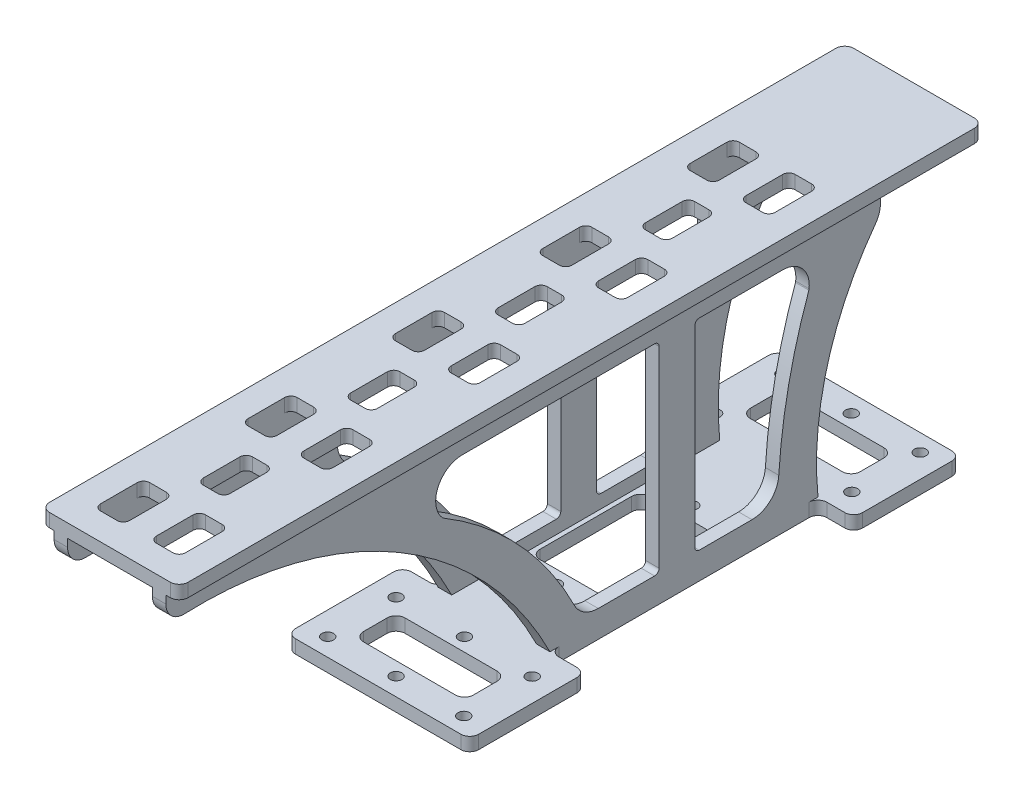
SolidWorks part; units mm, degrees
material "Plain Carbon Steel"
ref_plane "Front" through (0, 0, 0) normal (0, 0, 1) x (1, 0, 0)
ref_plane "Top" through (0, 0, 0) normal (0, 1, 0) x (1, 0, 0)
ref_plane "Right" through (0, 0, 0) normal (1, 0, 0) x (0, 0, -1)
sketch "Sketch1" plane through (0, 0, 0) normal (0, 0, 1) x (1, 0, 0)
  line L0 (0, 0) -> (205, 0)
  line L1 (205, 0) -> (205, 15)
  line L2 (205, 15) -> (180, 15)
  line L3 (180, 15) -> (180, 300)
  line L4 (180, 300) -> (25, 300)
  line L5 (25, 300) -> (25, 15)
  line L6 (25, 15) -> (0, 15)
  line L7 (0, 15) -> (0, 0)
  dimension "D1" = 205
  dimension "D2" = 15
  dimension "D3" = 15
  dimension "D4" = 25
  dimension "D5" = 25
  dimension "D6" = 300
extrude "Boss-Extrude1" add sketch "Sketch1" along normal blind 650
sketch "Sketch3" plane through (0, 0, 0) normal (0, -1, 0) x (1, 0, 0)
  line L0 (205, 325) -> (0, 325) construction
  line L1 (205, 650) -> (205, 0) construction
  line L2 (0, 650) -> (0, 0) construction
  circle A0 centre (26, 70.25) radius 6.5
  circle A1 centre (102.5, 70.25) radius 6.5
  circle A2 centre (178.997, 69.5778) radius 6.5
  circle A3 centre (178.997, 146.0778) radius 6.5
  circle A4 centre (102.5, 146.75) radius 6.5
  circle A5 centre (26, 146.75) radius 6.5
  circle A6 centre (26, 248.75) radius 6.5
  circle A7 centre (102.5, 248.75) radius 6.5
  circle A8 centre (102.5, 401.25) radius 6.5
  circle A9 centre (102.5, 503.25) radius 6.5
  circle A10 centre (178.997, 503.9222) radius 6.5
  circle A11 centre (178.997, 580.4222) radius 6.5
  circle A12 centre (102.5, 579.75) radius 6.5
  circle A13 centre (26, 401.25) radius 6.5
  circle A14 centre (26, 503.25) radius 6.5
  circle A15 centre (26, 579.75) radius 6.5
  dimension "D1" = 13
  dimension "D2" = 13
  dimension "D3" = 13
  dimension "D4" = 13
  dimension "D5" = 13
  dimension "D6" = 13
  dimension "D7" = 13
  dimension "D8" = 13
  dimension "D18" = 76.5
  dimension "D21" = 102.5
  dimension "D22" = 76.25
  dimension "D23" = 76.25
  dimension "D9" = 76.5
  dimension "D10" = 76.5
  dimension "D11" = 76.5
  dimension "D12" = 102
  dimension "D13" = 102
  dimension "D14" = 76.5
  dimension "D15" = 76.5
  dimension "D16" = 76.5
  dimension "D17" = 76.5
  dimension "D19" = 102.5
  dimension "D20" = 102.5
extrude "Cut-Extrude2" cut sketch "Sketch3" against normal blind 50
ref_plane "Plane1" through (40, 0, 0) normal (-1, 0, 0) x (0, 0, 1)
ref_plane "Plane2" through (102.5, 0, 0) normal (-1, 0, 0) x (0, 0, 1)
sketch "Sketch13" plane through (0, 0, 650) normal (0, 0, 1) x (1, 0, 0)
  line L0 (180, 15) -> (180, 300) construction
  line L1 (25, 300) -> (180, 300)
  line L2 (25, 300) -> (25, 285)
  line L3 (25, 285) -> (180, 285)
  line L4 (180, 300) -> (180, 285)
  dimension "D1" = 15
extrude "Boss-Extrude4" add sketch "Sketch13" along normal blind 250
sketch "Sketch15" plane through (205, 0, 0) normal (1, 0, 0) x (0, 0, -1)
  line L0 (0, 15) -> (0, 300) construction
  line L1 (-650, 15) -> (0, 15)
  line L2 (-650, 15) -> (-650, 285)
  line L3 (-650, 285) -> (0, 285)
  line L4 (0, 15) -> (0, 285)
  line L5 (-900, 300) -> (0, 300) construction
  dimension "D1" = 15
extrude "Cut-Extrude9" cut sketch "Sketch15" against normal blind 250
sketch "Sketch17" plane through (40, 0, 0) normal (-1, 0, 0) x (0, 0, 1)
  line L0 (100, 285) -> (100, 255)
  line L1 (0, 285) -> (900, 285) construction
  line L3 (170, 15) -> (470, 15)
  line L5 (900, 255) -> (900, 285)
  line L6 (900, 285) -> (100, 285)
  line L7 (650, 15) -> (0, 15) construction
  line L8 (0, 300) -> (0, 285) construction
  line L9 (0, 15) -> (0, 0) construction
  arc A0 (170, 15) -> (100, 255) centre (-162.4195, 48.2526) ccw
  arc A1 (470, 15) -> (900, 255) centre (861.8008, -181.7681) cw
  point P17 (0, 7.5)
  dimension "D1" = 30
  dimension "D2" = 30
  dimension "D3" = 300
  dimension "D4" = 0
  dimension "D5" = 100
  dimension "D6" = 170
extrude "Boss-Extrude5" add sketch "Sketch17" against normal blind 15
mirror "Mirror5" about plane through (102.5, 0, 0) normal (-1, 0, 0) of "Boss-Extrude5"
sketch "Sketch19" plane through (0, 0, 0) normal (0, -1, 0) x (1, 0, 0)
  line L0 (0, 0) -> (205, 0) construction
  line L1 (205, 0) -> (0, 0)
  line L2 (205, 0) -> (205, 50.25)
  line L3 (205, 50.25) -> (0, 50.25)
  line L4 (0, 0) -> (0, 50.25)
  line L5 (0, 650) -> (0, 0) construction
  line L7 (205, 650) -> (0, 650)
  line L8 (205, 650) -> (205, 599.75)
  line L9 (205, 599.75) -> (0, 599.75)
  line L10 (0, 650) -> (0, 599.75)
  circle A0 centre (102.5, 70.25) radius 6.5 construction
  circle A1 centre (102.5, 579.75) radius 6.5 construction
  dimension "D2" = 20
  dimension "D1" = 20
extrude "Cut-Extrude10" cut sketch "Sketch19" against normal blind 20
sketch "Sketch20" plane through (0, 15, 0) normal (0, 1, 0) x (1, 0, 0)
  line L0 (0, -599.75) -> (0, -50.25) construction
  line L1 (40, -170) -> (0, -170)
  line L2 (40, -170) -> (40, -470)
  line L3 (40, -470) -> (0, -470)
  line L4 (0, -170) -> (0, -470)
  line L5 (102.5, 8.25) -> (102.5, -8.25) construction
  line L6 (165, -470) -> (205, -470)
  line L7 (205, -170) -> (205, -470)
  line L8 (165, -170) -> (205, -170)
  line L9 (165, -170) -> (165, -470)
  dimension "D1" = 300
extrude "Cut-Extrude12" cut sketch "Sketch20" against normal blind 20
sketch "Sketch21" plane through (0, 0, 0) normal (0, -1, 0) x (1, 0, 0)
  line L3 (70, 263.75) -> (135, 263.75)
  line L6 (60, 273.75) -> (60, 376.25)
  line L7 (70, 386.25) -> (135, 386.25)
  line L8 (145, 273.75) -> (145, 376.25)
  line L16 (150, 171.75) -> (150, 223.75)
  line L17 (165, 170) -> (165, 470) construction
  line L18 (165, 900) -> (165, 100) construction
  line L19 (40, 900) -> (40, 100) construction
  line L21 (51, 85.25) -> (153.997, 85.25)
  line L22 (41, 95.25) -> (41, 121.75)
  line L23 (51, 131.75) -> (153.997, 131.75)
  line L24 (163.997, 95.25) -> (163.997, 121.75)
  line L25 (51, 518.25) -> (153.997, 518.25)
  line L26 (41, 528.25) -> (41, 554.75)
  line L27 (51, 564.75) -> (153.997, 564.75)
  line L28 (163.997, 528.25) -> (163.997, 554.75)
  circle A6 centre (102.5, 401.25) radius 6.5 construction
  arc A17 (135, 263.75) -> (145, 273.75) centre (135, 273.75) ccw
  arc A18 (60, 376.25) -> (70, 386.25) centre (70, 376.25) cw
  arc A19 (135, 386.25) -> (145, 376.25) centre (135, 376.25) cw
  arc A20 (70, 263.75) -> (60, 273.75) centre (70, 273.75) cw
  circle A21 centre (26, 70.25) radius 6.5 construction
  circle A22 centre (178.997, 69.5778) radius 6.5 construction
  circle A23 centre (102.5, 70.25) radius 6.5 construction
  circle A24 centre (102.5, 503.25) radius 6.5 construction
  circle A25 centre (178.997, 580.4222) radius 6.5 construction
  circle A26 centre (102.5, 579.75) radius 6.5 construction
  circle A27 centre (26, 503.25) radius 6.5 construction
  arc A28 (153.997, 518.25) -> (163.997, 528.25) centre (153.997, 528.25) ccw
  arc A29 (41, 554.75) -> (51, 564.75) centre (51, 554.75) cw
  arc A30 (153.997, 564.75) -> (163.997, 554.75) centre (153.997, 554.75) cw
  arc A31 (51, 518.25) -> (41, 528.25) centre (51, 528.25) cw
  arc A32 (153.997, 85.25) -> (163.997, 95.25) centre (153.997, 95.25) ccw
  arc A33 (41, 121.75) -> (51, 131.75) centre (51, 121.75) cw
  arc A34 (153.997, 131.75) -> (163.997, 121.75) centre (153.997, 121.75) cw
  arc A35 (51, 85.25) -> (41, 95.25) centre (51, 95.25) cw
  dimension "D18" = 15
  dimension "D21" = 15
  dimension "D22" = 10
  dimension "D2" = 15
  dimension "D3" = 20
  dimension "D6" = 20
  dimension "D8" = 15
  dimension "D14" = 15
  dimension "D15" = 15
  dimension "D16" = 15
  dimension "D19" = 15
  dimension "D20" = 15
sketch "Sketch22" plane through (40, 0, 0) normal (-1, 0, 0) x (0, 0, 1)
  line L1 (243.8256, 30) -> (415.9684, 30)
  line L3 (567.9389, 255) -> (209.7543, 255)
  line L4 (900, 285) -> (100, 285) construction
  line L5 (470, 0) -> (170, 0) construction
  line L7 (900, 255) -> (900, 285) construction
  arc A1 (590, 204.6701) -> (567.9389, 255) centre (567.9389, 225) ccw
  arc A3 (180, 221.1685) -> (209.7543, 255) centre (209.7543, 225) cw
  arc A4 (180, 221.1685) -> (213.8859, 58.0983) centre (-375.6301, 20.6529) cw
  arc A5 (442.8012, 46.5835) -> (590, 204.6701) centre (785.1, -124.5668) cw
  arc A6 (415.9684, 30) -> (442.8012, 46.5835) centre (415.9684, 60) ccw
  arc A7 (243.8256, 30) -> (213.8859, 58.0983) centre (243.8256, 60) cw
  point P3 (435, 30)
  point P19 (900, 270)
  point P25 (215, 30)
  dimension "D1" = 220
  dimension "D7" = 30
  dimension "D2" = 30
  dimension "D3" = 30
  dimension "D4" = 80
  dimension "D5" = 310
  dimension "D6" = 45
extrude "Cut-Extrude14" cut sketch "Sketch22" against normal through all
fillet "Fillet1" radius 20 2 edges at (157.5, 255, 900) (47.5, 255, 900)
fillet "Fillet2" radius 30 2 edges at (47.5, 255, 100) (157.5, 255, 100)
sketch "Sketch24" plane through (0, 300, 0) normal (0, 1, 0) x (1, 0, 0)
  line L0 (180, -900) -> (180, 0) construction
  line L5 (143, -870) -> (124.5, -870)
  line L6 (150, -863) -> (150, -822)
  line L7 (143, -815) -> (124.5, -815)
  line L8 (117.5, -863) -> (117.5, -822)
  line L9 (62, -870) -> (80.5, -870)
  line L10 (55, -863) -> (55, -822)
  line L11 (62, -815) -> (80.5, -815)
  line L12 (87.5, -863) -> (87.5, -822)
  line L21 (25, -900) -> (25, 0) construction
  line L22 (55, -698) -> (55, -657)
  line L23 (62, -705) -> (80.5, -705)
  line L24 (87.5, -698) -> (87.5, -657)
  line L25 (62, -650) -> (80.5, -650)
  line L26 (150, -698) -> (150, -657)
  line L27 (143, -705) -> (124.5, -705)
  line L28 (117.5, -698) -> (117.5, -657)
  line L29 (143, -650) -> (124.5, -650)
  line L30 (55, -533) -> (55, -492)
  line L31 (62, -540) -> (80.5, -540)
  line L32 (87.5, -533) -> (87.5, -492)
  line L33 (62, -485) -> (80.5, -485)
  line L34 (150, -533) -> (150, -492)
  line L35 (143, -540) -> (124.5, -540)
  line L36 (117.5, -533) -> (117.5, -492)
  line L37 (143, -485) -> (124.5, -485)
  line L38 (55, -368) -> (55, -327)
  line L39 (62, -375) -> (80.5, -375)
  line L40 (87.5, -368) -> (87.5, -327)
  line L41 (62, -320) -> (80.5, -320)
  line L42 (150, -368) -> (150, -327)
  line L43 (143, -375) -> (124.5, -375)
  line L44 (117.5, -368) -> (117.5, -327)
  line L45 (143, -320) -> (124.5, -320)
  line L46 (55, -203) -> (55, -162)
  line L47 (62, -210) -> (80.5, -210)
  line L48 (87.5, -203) -> (87.5, -162)
  line L49 (62, -155) -> (80.5, -155)
  line L50 (150, -203) -> (150, -162)
  line L51 (143, -210) -> (124.5, -210)
  line L52 (117.5, -203) -> (117.5, -162)
  line L53 (143, -155) -> (124.5, -155)
  line L54 (180, -900) -> (25, -900) construction
  line L55 (117.5, -574.5) -> (117.5, -615.5)
  line L56 (110.5, -732.5) -> (94.5, -732.5)
  line L57 (117.5, -739.5) -> (117.5, -780.5)
  line L58 (110.5, -787.5) -> (94.5, -787.5)
  line L59 (87.5, -739.5) -> (87.5, -780.5)
  line L60 (110.5, -567.5) -> (94.5, -567.5)
  line L61 (87.5, -574.5) -> (87.5, -615.5)
  line L62 (110.5, -622.5) -> (94.5, -622.5)
  line L63 (117.5, -409.5) -> (117.5, -450.5)
  line L64 (110.5, -402.5) -> (94.5, -402.5)
  line L65 (87.5, -409.5) -> (87.5, -450.5)
  line L66 (110.5, -457.5) -> (94.5, -457.5)
  line L67 (117.5, -244.5) -> (117.5, -285.5)
  line L68 (110.5, -237.5) -> (94.5, -237.5)
  line L69 (87.5, -244.5) -> (87.5, -285.5)
  line L70 (110.5, -292.5) -> (94.5, -292.5)
  arc A0 (94.5, -237.5) -> (87.5, -244.5) centre (94.5, -244.5) ccw
  arc A1 (117.5, -285.5) -> (110.5, -292.5) centre (110.5, -285.5) cw
  arc A2 (87.5, -285.5) -> (94.5, -292.5) centre (94.5, -285.5) ccw
  arc A3 (117.5, -244.5) -> (110.5, -237.5) centre (110.5, -244.5) ccw
  arc A4 (94.5, -402.5) -> (87.5, -409.5) centre (94.5, -409.5) ccw
  arc A5 (117.5, -450.5) -> (110.5, -457.5) centre (110.5, -450.5) cw
  arc A6 (87.5, -450.5) -> (94.5, -457.5) centre (94.5, -450.5) ccw
  arc A7 (117.5, -409.5) -> (110.5, -402.5) centre (110.5, -409.5) ccw
  arc A8 (94.5, -567.5) -> (87.5, -574.5) centre (94.5, -574.5) ccw
  arc A9 (117.5, -615.5) -> (110.5, -622.5) centre (110.5, -615.5) cw
  arc A10 (87.5, -615.5) -> (94.5, -622.5) centre (94.5, -615.5) ccw
  arc A11 (117.5, -574.5) -> (110.5, -567.5) centre (110.5, -574.5) ccw
  arc A12 (94.5, -732.5) -> (87.5, -739.5) centre (94.5, -739.5) ccw
  arc A13 (117.5, -780.5) -> (110.5, -787.5) centre (110.5, -780.5) cw
  arc A14 (94.5, -787.5) -> (87.5, -780.5) centre (94.5, -780.5) cw
  arc A15 (110.5, -732.5) -> (117.5, -739.5) centre (110.5, -739.5) cw
  arc A16 (80.5, -210) -> (87.5, -203) centre (80.5, -203) ccw
  arc A17 (55, -162) -> (62, -155) centre (62, -162) cw
  arc A18 (87.5, -162) -> (80.5, -155) centre (80.5, -162) ccw
  arc A19 (55, -203) -> (62, -210) centre (62, -203) ccw
  arc A20 (124.5, -210) -> (117.5, -203) centre (124.5, -203) cw
  arc A21 (150, -162) -> (143, -155) centre (143, -162) ccw
  arc A22 (117.5, -162) -> (124.5, -155) centre (124.5, -162) cw
  arc A23 (150, -203) -> (143, -210) centre (143, -203) cw
  arc A24 (80.5, -375) -> (87.5, -368) centre (80.5, -368) ccw
  arc A25 (55, -327) -> (62, -320) centre (62, -327) cw
  arc A26 (87.5, -327) -> (80.5, -320) centre (80.5, -327) ccw
  arc A27 (55, -368) -> (62, -375) centre (62, -368) ccw
  arc A28 (124.5, -375) -> (117.5, -368) centre (124.5, -368) cw
  arc A29 (150, -327) -> (143, -320) centre (143, -327) ccw
  arc A30 (117.5, -327) -> (124.5, -320) centre (124.5, -327) cw
  arc A31 (150, -368) -> (143, -375) centre (143, -368) cw
  arc A32 (80.5, -540) -> (87.5, -533) centre (80.5, -533) ccw
  arc A33 (55, -492) -> (62, -485) centre (62, -492) cw
  arc A34 (87.5, -492) -> (80.5, -485) centre (80.5, -492) ccw
  arc A35 (55, -533) -> (62, -540) centre (62, -533) ccw
  arc A36 (124.5, -540) -> (117.5, -533) centre (124.5, -533) cw
  arc A37 (150, -492) -> (143, -485) centre (143, -492) ccw
  arc A38 (117.5, -492) -> (124.5, -485) centre (124.5, -492) cw
  arc A39 (150, -533) -> (143, -540) centre (143, -533) cw
  arc A40 (80.5, -705) -> (87.5, -698) centre (80.5, -698) ccw
  arc A41 (55, -657) -> (62, -650) centre (62, -657) cw
  arc A42 (87.5, -657) -> (80.5, -650) centre (80.5, -657) ccw
  arc A43 (55, -698) -> (62, -705) centre (62, -698) ccw
  arc A44 (124.5, -705) -> (117.5, -698) centre (124.5, -698) cw
  arc A45 (150, -657) -> (143, -650) centre (143, -657) ccw
  arc A46 (117.5, -657) -> (124.5, -650) centre (124.5, -657) cw
  arc A47 (150, -698) -> (143, -705) centre (143, -698) cw
  arc A48 (80.5, -870) -> (87.5, -863) centre (80.5, -863) ccw
  arc A49 (55, -822) -> (62, -815) centre (62, -822) cw
  arc A50 (80.5, -815) -> (87.5, -822) centre (80.5, -822) cw
  arc A51 (62, -870) -> (55, -863) centre (62, -863) cw
  arc A52 (124.5, -870) -> (117.5, -863) centre (124.5, -863) cw
  arc A53 (150, -822) -> (143, -815) centre (143, -822) ccw
  arc A54 (124.5, -815) -> (117.5, -822) centre (124.5, -822) ccw
  arc A55 (143, -870) -> (150, -863) centre (143, -863) ccw
  point P88 (87.5, -732.5)
  point P91 (117.5, -787.5)
  point P96 (117.5, -732.5)
  point P165 (55, -815)
  point P170 (55, -870)
  point P175 (150, -815)
  point P178 (117.5, -815)
  point P181 (150, -870)
  dimension "D16" = 7
  dimension "D1" = 30
  dimension "D2" = 30
  dimension "D3" = 30
  dimension "D4" = 32.5
  dimension "D5" = 5
  dimension "D6" = 30
  dimension "D7" = 30
  dimension "D8" = 55
  dimension "D9" = 55
  dimension "D10" = 55
  dimension "D11" = 30
  dimension "D12" = 62.5
  dimension "D13" = 27.5
  dimension "D14" = 27.5
  dimension "D15" = 4
extrude "Cut-Extrude15" cut sketch "Sketch24" against normal blind 20
extrude "Cut-Extrude16" cut sketch "Sketch21" against normal blind 20 contours A35 L21 A32 L24 A34 L23 A33 L22 | A20 L3 A17 L8 A19 L7 A18 L6 | A31 L25 A28 L28 A30 L27 A29 L26
fillet "Fillet4" radius 10 12 edges at (205, 7.5, 599.75) (205, 7.5, 470) (165, 7.5, 470) (165, 7.5, 170) (205, 7.5, 170) (205, 7.5, 50.25) (0, 7.5, 50.25) (0, 7.5, 170) (40, 7.5, 170) (40, 7.5, 470) (0, 7.5, 470) (0, 7.5, 599.75)
fillet "Fillet5" radius 10 4 edges at (180, 292.5, 0) (180, 292.5, 900) (25, 292.5, 0) (25, 292.5, 900)
sketch "Sketch25" plane through (40, 0, 0) normal (-1, 0, 0) x (0, 0, 1)
  line L0 (243.8256, 30) -> (415.9684, 30) construction
  line L1 (347.8859, 30) -> (307.8859, 30)
  line L2 (347.8859, 30) -> (347.8859, 255)
  line L3 (347.8859, 255) -> (307.8859, 255)
  line L4 (307.8859, 30) -> (307.8859, 255)
  line L5 (567.9389, 255) -> (209.7543, 255) construction
  dimension "D1" = 40
  dimension "D2" = 94
extrude "Boss-Extrude6" add sketch "Sketch25" against normal blind 15
fillet "Fillet6" radius 5 6 edges at (47.5, 221.1685, 180) (47.5, 30, 307.8859) (47.5, 255, 347.8859) (47.5, 204.6701, 590) (47.5, 30, 347.8859) (47.5, 255, 307.8859)
mirror "Mirror6" about plane through (102.5, 0, 0) normal (-1, 0, 0) of "Boss-Extrude6"
fillet "Fillet7" radius 5 6 edges at (157.5, 204.6701, 590) (157.5, 30, 347.8859) (157.5, 221.1685, 180) (157.5, 30, 307.8859) (157.5, 255, 307.8859) (157.5, 255, 347.8859)
